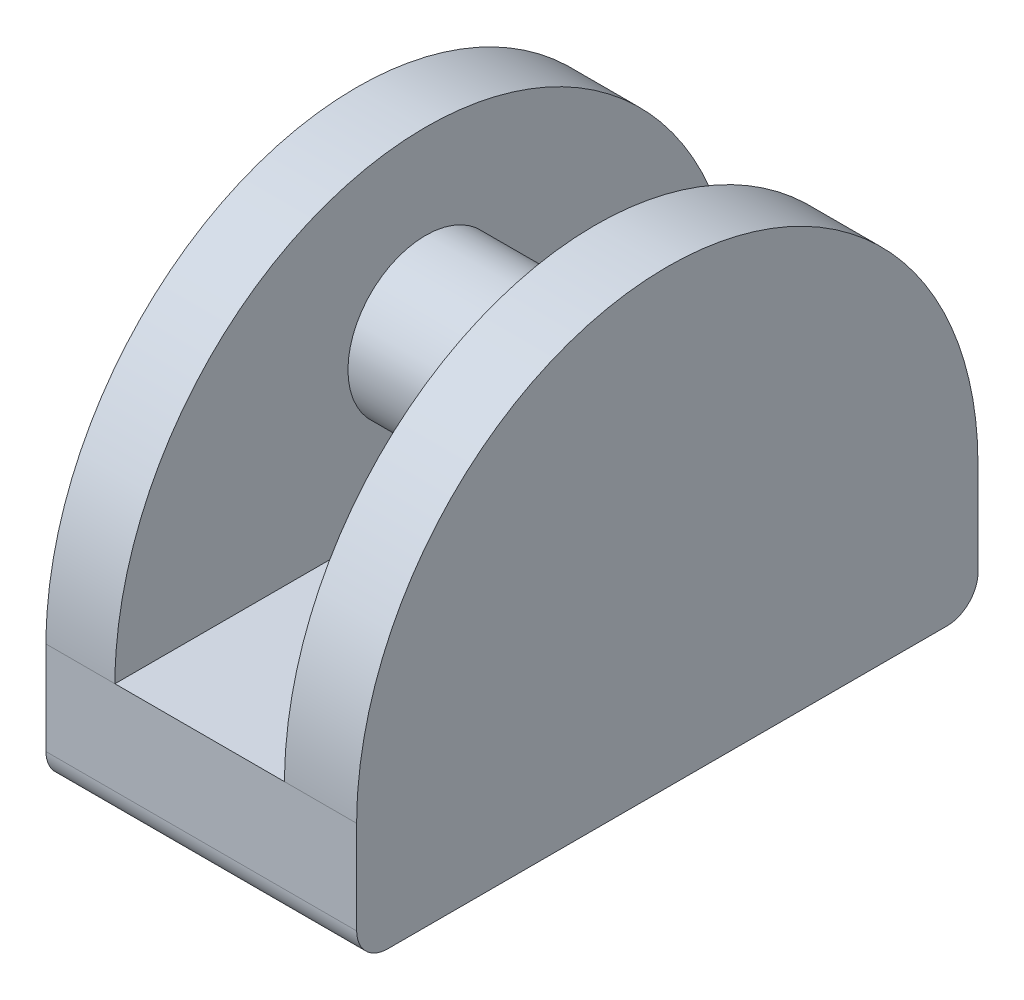
SolidWorks part; units mm, degrees
ref_plane "Front Plane" through (0, 0, 0) normal (0, 0, 1) x (1, 0, 0)
ref_plane "Top Plane" through (0, 0, 0) normal (0, 1, 0) x (1, 0, 0)
ref_plane "Right Plane" through (0, 0, 0) normal (1, 0, 0) x (0, 0, -1)
sketch "Sketch1" plane through (0, 0, 0) normal (1, 0, 0) x (0, 0, -1)
  line L1 (0, 0) -> (10, 0)
  line L2 (0, 0) -> (0, -2)
  line L3 (0, -2) -> (10, -2)
  line L4 (10, 0) -> (10, -2)
  dimension "D1" = 10
  dimension "D2" = 2
extrude "Boss-Extrude1" add sketch "Sketch1" along normal blind 5
sketch "Sketch3" plane through (0, 0, 0) normal (1, 0, 0) x (0, 0, -1)
  line L0 (10, 0) -> (0, 0) construction
  line L1 (0, 0) -> (10, 0)
  ellipse E0 centre (5, 0) end of major axis (5, -5.2583) minor radius 5 (10, 0) -> (0, 0) ccw
extrude "Boss-Extrude2" add sketch "Sketch3" along normal blind 5
sketch "Sketch4" plane through (0, 0, 0) normal (0, 1, 0) x (1, 0, 0)
  line L0 (5, 10) -> (0, 10) construction
  line L1 (1.1097, 10) -> (3.8393, 10)
  line L2 (1.1097, 10) -> (1.1097, 0)
  line L3 (1.1097, 0) -> (3.8393, 0)
  line L4 (3.8393, 10) -> (3.8393, 0)
  line L5 (5, 0) -> (0, 0) construction
extrude "Cut-Extrude1" cut sketch "Sketch4" along normal blind 6
sketch "Sketch5" plane through (0, 0, 0) normal (-1, 0, 0) x (0, 0, 1)
  line L0 (0, 0) -> (0, -2) construction
  line L1 (-10, 0) -> (0, 0) construction
  circle A0 centre (-5, 2.5) radius 1.25
  dimension "D1" = 2.5
  dimension "D2" = 5
  dimension "D3" = 2.5
extrude "Boss-Extrude3" add sketch "Sketch5" against normal blind 5
fillet "Fillet1" radius 0.5 2 edges at (2.5, -2, 0) (2.5, -2, -10)
